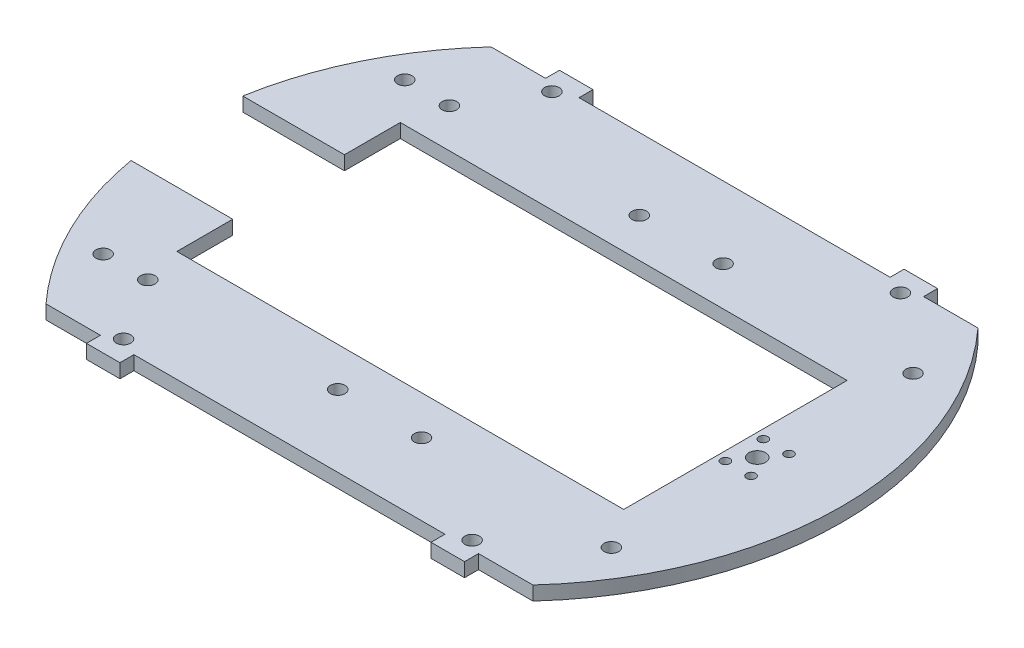
SolidWorks part; units mm, degrees
material "Acrylic (Medium-high impact)"
ref_plane "Front Plane" through (0, 0, 0) normal (0, 0, 1) x (1, 0, 0)
ref_plane "Top Plane" through (0, 0, 0) normal (0, 1, 0) x (1, 0, 0)
ref_plane "Right Plane" through (0, 0, 0) normal (1, 0, 0) x (0, 0, -1)
sketch "Sketch1" plane through (0, 0, 0) normal (0, 1, 0) x (1, 0, 0)
  line L0 (-73.9169, 12.7) -> (-73.9169, -12.7)
  line L1 (-35.3642, -50.6035) -> (-35.3642, -53.7785)
  line L2 (-55.356, -50.6035) -> (-42.9842, -50.6035)
  line L3 (-55.356, 50.6035) -> (-42.9842, 50.6035)
  line L4 (-48.5169, -34.29) -> (-48.5169, 34.29) construction
  line L5 (-48.5169, 34.29) -> (-5.3369, 34.29) construction
  line L6 (-5.3369, 34.29) -> (-5.3369, -34.29) construction
  line L7 (-5.3369, -34.29) -> (-48.5169, -34.29) construction
  line L8 (-73.9169, 0) -> (-48.5169, 0) construction
  line L9 (0, 50.6035) -> (0, -49.0013) construction
  line L10 (-73.9169, 12.7) -> (-73.9169, -12.7) construction
  line L11 (-50.8, 25.4) -> (50.8, 25.4)
  line L12 (-50.8, 25.4) -> (-50.8, -25.4)
  line L13 (-50.8, -25.4) -> (50.8, -25.4)
  line L14 (50.8, 25.4) -> (50.8, -25.4)
  line L15 (0, 0) -> (0, 25.4) construction
  line L16 (0, 0) -> (-50.8, 0) construction
  line L17 (13.7131, 34.29) -> (13.7131, -34.29) construction
  line L18 (13.7131, -34.29) -> (56.8931, -34.29) construction
  line L19 (56.8931, -34.29) -> (56.8931, 34.29) construction
  line L20 (56.8931, 34.29) -> (13.7131, 34.29) construction
  line L21 (39.6269, 48.6985) -> (39.6269, 50.6035) construction
  line L22 (39.6269, -48.6985) -> (39.6269, -50.6035) construction
  line L23 (-39.6269, -48.6985) -> (-39.6269, -50.6035) construction
  line L24 (-39.6269, 48.6985) -> (-39.6269, 50.6035) construction
  line L25 (39.6269, 48.6985) -> (41.2779, 48.6985) construction
  line L26 (39.6269, -48.6985) -> (41.2779, -48.6985) construction
  line L27 (-35.3642, -50.6035) -> (35.3642, -50.6035)
  line L28 (35.3642, -50.6035) -> (35.3642, -53.7785)
  line L29 (35.3642, -53.7785) -> (42.9842, -53.7785)
  line L30 (42.9842, -50.6035) -> (42.9842, -53.7785)
  line L31 (-35.3642, -53.7785) -> (-42.9842, -53.7785)
  line L32 (-42.9842, -50.6035) -> (-42.9842, -53.7785)
  line L33 (42.9842, 50.6035) -> (42.9842, 53.7785)
  line L34 (35.3642, 53.7785) -> (42.9842, 53.7785)
  line L35 (35.3642, 50.6035) -> (35.3642, 53.7785)
  line L36 (-35.3642, 50.6035) -> (-35.3642, 53.7785)
  line L37 (-35.3642, 53.7785) -> (-42.9842, 53.7785)
  line L38 (-42.9842, 50.6035) -> (-42.9842, 53.7785)
  line L39 (42.9842, -50.6035) -> (55.356, -50.6035)
  line L40 (42.9842, 50.6035) -> (55.356, 50.6035)
  line L41 (-35.3642, 50.6035) -> (35.3642, 50.6035)
  line L42 (50.8, 6.35) -> (60.7031, 6.35) construction
  line L43 (60.7031, -38.1) -> (60.7031, 38.1) construction
  line L44 (60.7031, 6.35) -> (60.7031, -6.35) construction
  line L45 (60.7031, -6.35) -> (50.8, -6.35) construction
  line L46 (60.7031, 0) -> (50.8, 0) construction
  line L47 (58.6711, 4.318) -> (58.6711, -4.318) construction
  line L48 (58.6711, -4.318) -> (52.832, -4.318) construction
  line L49 (52.832, -4.318) -> (52.832, 4.318) construction
  line L50 (52.832, 4.318) -> (58.6711, 4.318) construction
  line L51 (58.6711, 4.318) -> (58.6711, 6.35) construction
  line L52 (58.6711, 4.318) -> (60.7031, 4.318) construction
  line L53 (52.832, 4.318) -> (52.832, 6.35) construction
  line L54 (52.832, 4.318) -> (50.8, 4.318) construction
  line L55 (52.832, -4.318) -> (52.832, -6.35) construction
  line L56 (52.832, -4.318) -> (50.8, -4.318) construction
  line L57 (58.6711, -4.318) -> (58.6711, -6.35) construction
  line L58 (58.6711, -4.318) -> (60.7031, -4.318) construction
  arc A0 (-73.9169, -12.7) -> (-55.356, -50.6035) centre (0, 0) ccw
  circle A1 centre (13.7131, 34.29) radius 1.651
  arc A2 (-55.356, 50.6035) -> (-73.9169, 12.7) centre (0, 0) ccw
  arc A3 (55.356, -50.6035) -> (55.356, 50.6035) centre (0, 0) ccw
  circle A4 centre (-58.6769, -34.29) radius 1.651
  circle A5 centre (-58.6769, 34.29) radius 1.651
  circle A6 centre (-39.6269, 48.6985) radius 1.651
  circle A7 centre (39.6269, 48.6985) radius 1.651
  circle A8 centre (-39.6269, -48.6985) radius 1.651
  circle A9 centre (39.6269, -48.6985) radius 1.651
  circle A10 centre (56.8931, 34.29) radius 1.651
  circle A11 centre (-58.6769, 34.29) radius 1.651 construction
  circle A12 centre (-48.5169, 34.29) radius 1.651
  circle A13 centre (-5.3369, 34.29) radius 1.651
  circle A14 centre (-5.3369, -34.29) radius 1.651
  circle A15 centre (-48.5169, -34.29) radius 1.651
  circle A16 centre (13.7131, -34.29) radius 1.651
  circle A17 centre (56.8931, -34.29) radius 1.651
  circle A18 centre (55.7515, 0) radius 1.905
  circle A19 centre (58.6711, 4.318) radius 1.016
  circle A20 centre (58.6711, -4.318) radius 1.016
  circle A21 centre (52.832, -4.318) radius 1.016
  circle A22 centre (52.832, 4.318) radius 1.016
  dimension "D3" = 3.302
  dimension "D8" = 3.81
  dimension "D11" = 2.032
  dimension "D1" = 43.18
  dimension "D2" = 68.58
  dimension "D4" = 25.4
  dimension "D5" = 101.6
  dimension "D6" = 50.8
  dimension "D7" = 19.05
  dimension "D9" = 12.7
  dimension "D10" = 19.05
  dimension "D12" = 2.032
extrude "Boss-Extrude1" add sketch "Sketch1" along normal blind 3.175
sketch "Sketch3" plane through (0, 3.175, 0) normal (0, 1, 0) x (1, 0, 0)
  line L0 (-50.8, 25.4) -> (-50.8, -25.4) construction
  line L1 (-73.9169, 12.7) -> (-50.8, 12.7)
  line L2 (-73.9169, 12.7) -> (-73.9169, -12.7)
  line L3 (-73.9169, -12.7) -> (-50.8, -12.7)
  line L4 (-50.8, 12.7) -> (-50.8, -12.7)
extrude "Cut-Extrude2" cut sketch "Sketch3" against normal up to surface (3.175 mm away) up to face at (52.832, 0, 5.334)
